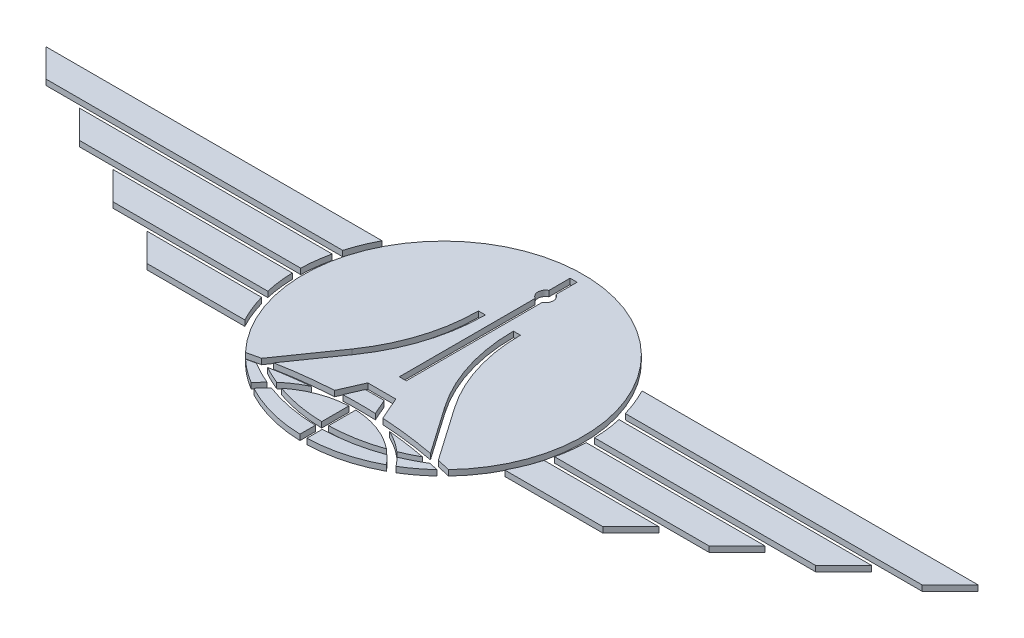
SolidWorks part; units mm, degrees
ref_plane "前视基准面" through (0, 0, 0) normal (0, 0, 1) x (1, 0, 0)
ref_plane "上视基准面" through (0, 0, 0) normal (0, 1, 0) x (1, 0, 0)
ref_plane "右视基准面" through (0, 0, 0) normal (1, 0, 0) x (0, 0, -1)
sketch "草图1" plane through (0, 0, 0) normal (0, 1, 0) x (1, 0, 0)
  line L0 (0, 72.9714) -> (0, -201.2593) construction
  line L1 (5, -22) -> (-5, -22)
  line L2 (-5, -22) -> (-8.6038, -30.247)
  line L3 (5, -22) -> (8.6038, -30.247)
  line L4 (3.3642, -24.5) -> (5.817, -30.1128)
  line L5 (3.3642, -24.5) -> (-3.3642, -24.5)
  line L6 (-3.3642, -24.5) -> (-5.817, -30.1128)
  line L7 (-1.25, 46.4832) -> (-1.25, 38.9495)
  line L8 (-3.3642, -24.5) -> (-6.313, -31.248) construction
  line L9 (3.3642, -24.5) -> (6.313, -31.248) construction
  line L10 (1.25, 46.4832) -> (1.25, 38.9495)
  line L11 (-1.25, -32.5261) -> (-1.25, -42.2364)
  line L12 (1.25, -32.5261) -> (1.25, -42.2364)
  line L13 (-1.25, 72.9714) -> (-1.25, -201.2593) construction
  line L14 (-1.25, -14.5) -> (1.25, -14.5)
  line L15 (1.25, 72.9714) -> (1.25, -201.2593) construction
  line L16 (1.25, -44.4869) -> (1.25, -49.9844)
  line L17 (-1.25, -44.4869) -> (-1.25, -49.9844)
  line L18 (-1.25, 34.0505) -> (-1.25, -14.5)
  line L19 (1.25, 34.0505) -> (1.25, -14.5)
  line L20 (-141.775, 20) -> (140.8827, 20) construction
  line L21 (-28, -32.6365) -> (-16.2201, -15.7298)
  line L22 (-31.5476, -33.355) -> (-18.2713, -14.3006)
  line L23 (-30.0512, -31.2073) -> (-18.2713, -14.3006) construction
  line L24 (-7.5, 20) -> (-5, 20)
  line L25 (28, -32.6365) -> (16.2201, -15.7298)
  line L26 (31.5476, -33.355) -> (18.2713, -14.3006)
  line L27 (7.5, 20) -> (5, 20)
  arc A0 (-34.1612, -36.5104) -> (-25.8488, -42.8) centre (0, 0) ccw
  arc A2 (36.2433, -34.4444) -> (31.5476, -33.355) centre (0, -180) ccw
  arc A3 (34.1612, -36.5104) -> (30.9902, -35.7923) centre (0, -180) ccw
  arc A4 (36.2433, -34.4444) -> (-36.2433, -34.4444) centre (0, 0) ccw
  arc A5 (35.6393, -36.8704) -> (-35.6393, -36.8704) centre (0, -180) ccw construction
  arc A6 (-8.6038, -30.247) -> (-28, -32.6365) centre (0, -180) ccw
  arc A7 (5.817, -30.1128) -> (-5.817, -30.1128) centre (0, -180) ccw
  arc A8 (36.2433, -34.4444) -> (-36.2433, -34.4444) centre (0, -180) ccw construction
  arc A9 (-13.9893, -33.1649) -> (-27.6708, -35.1188) centre (0, -180) ccw
  arc A10 (1.25, -49.9844) -> (23.6558, -44.05) centre (0, 0) ccw
  arc A12 (1.25, 46.4832) -> (-1.25, 46.4832) centre (0, 0) ccw
  arc A13 (-1.25, 38.9495) -> (-1.25, 34.0505) centre (0, 36.5) ccw
  arc A14 (1.25, 34.0505) -> (1.25, 38.9495) centre (0, 36.5) ccw
  arc A16 (-16.2201, -15.7298) -> (-5, 20) centre (-67.5, 20) ccw
  arc A17 (-18.2713, -14.3006) -> (-7.5, 20) centre (-67.5, 20) ccw
  arc A18 (16.2201, -15.7298) -> (5, 20) centre (67.5, 20) cw
  arc A19 (18.2713, -14.3006) -> (7.5, 20) centre (67.5, 20) cw
  arc A20 (-31.5476, -33.355) -> (-36.2433, -34.4444) centre (0, -180) ccw
  arc A21 (28, -32.6365) -> (8.6038, -30.247) centre (0, -180) ccw
  arc A22 (-27.6708, -35.1188) -> (-21.4468, -38.081) centre (0, 15) ccw
  arc A23 (-30.9902, -35.7923) -> (-23.2349, -39.7758) centre (0, 15) ccw
  arc A24 (-20.6981, -40.7839) -> (-23.6558, -44.05) centre (0, -62.5) ccw
  arc A25 (27.6708, -35.1188) -> (13.9893, -33.1649) centre (0, -180) ccw
  arc A26 (1.25, -42.2364) -> (18.7598, -39.0891) centre (0, 15) ccw
  arc A27 (1.25, -44.4869) -> (20.6981, -40.7839) centre (0, 15) ccw
  arc A28 (-30.9902, -35.7923) -> (-34.1612, -36.5104) centre (0, -180) ccw
  arc A29 (-13.9893, -33.1649) -> (-21.4468, -38.081) centre (0, -62.5) ccw
  arc A30 (-18.7598, -39.0891) -> (-1.25, -42.2364) centre (0, 15) ccw
  circle A31 centre (0, -62.5) radius 32.5 construction
  arc A32 (-23.2349, -39.7758) -> (-25.8488, -42.8) centre (0, -62.5) ccw
  arc A33 (-20.6981, -40.7839) -> (-1.25, -44.4869) centre (0, 15) ccw
  arc A34 (-23.6558, -44.05) -> (-1.25, -49.9844) centre (0, 0) ccw
  circle A35 centre (0, -62.5) radius 30 construction
  arc A36 (25.8488, -42.8) -> (23.2349, -39.7758) centre (0, -62.5) ccw
  arc A37 (23.6558, -44.05) -> (20.6981, -40.7839) centre (0, -62.5) ccw
  arc A38 (-1.25, -32.5261) -> (-18.7598, -39.0891) centre (0, -62.5) ccw
  arc A39 (21.4468, -38.081) -> (27.6708, -35.1188) centre (0, 15) ccw
  arc A40 (18.7598, -39.0891) -> (1.25, -32.5261) centre (0, -62.5) ccw
  arc A41 (21.4468, -38.081) -> (13.9893, -33.1649) centre (0, -62.5) ccw
  arc A42 (23.2349, -39.7758) -> (30.9902, -35.7923) centre (0, 15) ccw
  arc A43 (25.8488, -42.8) -> (34.1612, -36.5104) centre (0, 0) ccw
  point P17 (0, -22)
  point P72 (32.5, -62.5)
  point P79 (28.6891, -53.7288)
  dimension "D1" = 100
  dimension "D2" = 300
  dimension "D12" = 46.5
  dimension "D13" = 5.5
  dimension "D16" = 62.5
  dimension "D20" = 15
  dimension "D21" = 114.5
  dimension "D22" = 119
  dimension "D23" = 60
  dimension "D3" = 180
  dimension "D5" = 5
  dimension "D6" = 9
  dimension "D10" = 7.5
  dimension "D11" = 22
  dimension "D14" = 36.5
  dimension "D15" = 20
  dimension "D17" = 67.5
  dimension "D18" = 28
  dimension "D19" = 2.5
  dimension "D4" = 2.5
  dimension "D7" = 2.5
  dimension "D8" = 1.25
  dimension "D9" = 1.25
  dimension "D24" = 2.5
extrude "凸台-拉伸2" add sketch "草图1" along normal blind 2
sketch "草图2" plane through (0, 2, 0) normal (0, 1, 0) x (1, 0, 0)
  line L0 (-97.5595, 0) -> (99.0923, 0) construction
  line L1 (0, 84.05) -> (0, -100.8615) construction
  line L2 (141.4327, 11.5) -> (131.4327, 1.5)
  line L3 (131.4327, 1.5) -> (52.4786, 1.5)
  line L4 (-156.4327, 14.5) -> (-50.4579, 14.5)
  line L5 (-166.4327, 24.5) -> (-46.4327, 24.5)
  line L6 (141.4327, 11.5) -> (51.225, 11.5)
  line L7 (116.4327, -1.5) -> (106.4327, -11.5)
  line L8 (106.4327, -11.5) -> (51.225, -11.5)
  line L9 (116.4327, -1.5) -> (52.4786, -1.5)
  line L10 (-166.4327, 24.5) -> (-156.4327, 14.5)
  line L11 (91.4327, -14.5) -> (81.4327, -24.5)
  line L12 (-166.4327, 24.5) -> (73.1045, 24.5) construction
  line L13 (91.4327, -14.5) -> (50.4579, -14.5)
  line L14 (-166.4327, 14.5) -> (73.1045, 14.5) construction
  line L15 (81.4327, -24.5) -> (46.4327, -24.5)
  line L16 (166.4327, 24.5) -> (156.4327, 14.5)
  line L17 (-81.4327, -24.5) -> (-46.4327, -24.5)
  line L18 (166.4327, 24.5) -> (46.4327, 24.5)
  line L19 (-91.4327, -14.5) -> (-50.4579, -14.5)
  line L20 (-91.4327, -14.5) -> (-81.4327, -24.5)
  line L21 (-116.4327, -1.5) -> (-52.4786, -1.5)
  line L22 (-106.4327, -11.5) -> (-51.225, -11.5)
  line L23 (156.4327, 14.5) -> (50.4579, 14.5)
  line L24 (-116.4327, -1.5) -> (-106.4327, -11.5)
  line L25 (-141.4327, 11.5) -> (-51.225, 11.5)
  line L26 (-131.4327, 1.5) -> (-52.4786, 1.5)
  line L27 (-141.4327, 11.5) -> (-131.4327, 1.5)
  arc A0 (-46.4327, 24.5) -> (-50.4579, 14.5) centre (0, 0) ccw
  arc A1 (-51.225, 11.5) -> (-52.4786, 1.5) centre (0, 0) ccw
  arc A2 (-52.4786, -1.5) -> (-51.225, -11.5) centre (0, 0) ccw
  arc A3 (-50.4579, -14.5) -> (-46.4327, -24.5) centre (0, 0) ccw
  arc A4 (50.4579, -14.5) -> (46.4327, -24.5) centre (0, 0) cw
  arc A5 (52.4786, -1.5) -> (51.225, -11.5) centre (0, 0) cw
  arc A6 (51.225, 11.5) -> (52.4786, 1.5) centre (0, 0) cw
  arc A7 (46.4327, 24.5) -> (50.4579, 14.5) centre (0, 0) cw
  point P7 (-166.4327, 1.5)
  point P8 (73.1045, 1.5)
  point P9 (-166.4327, 11.5)
  point P10 (73.1045, 11.5)
  dimension "D1" = 105
  dimension "D2" = 1.5
  dimension "D3" = 10
  dimension "D6" = 120
  dimension "D7" = 45
  dimension "D5" = 10
extrude "凸台-拉伸3" add sketch "草图2" against normal blind 2 separate body
